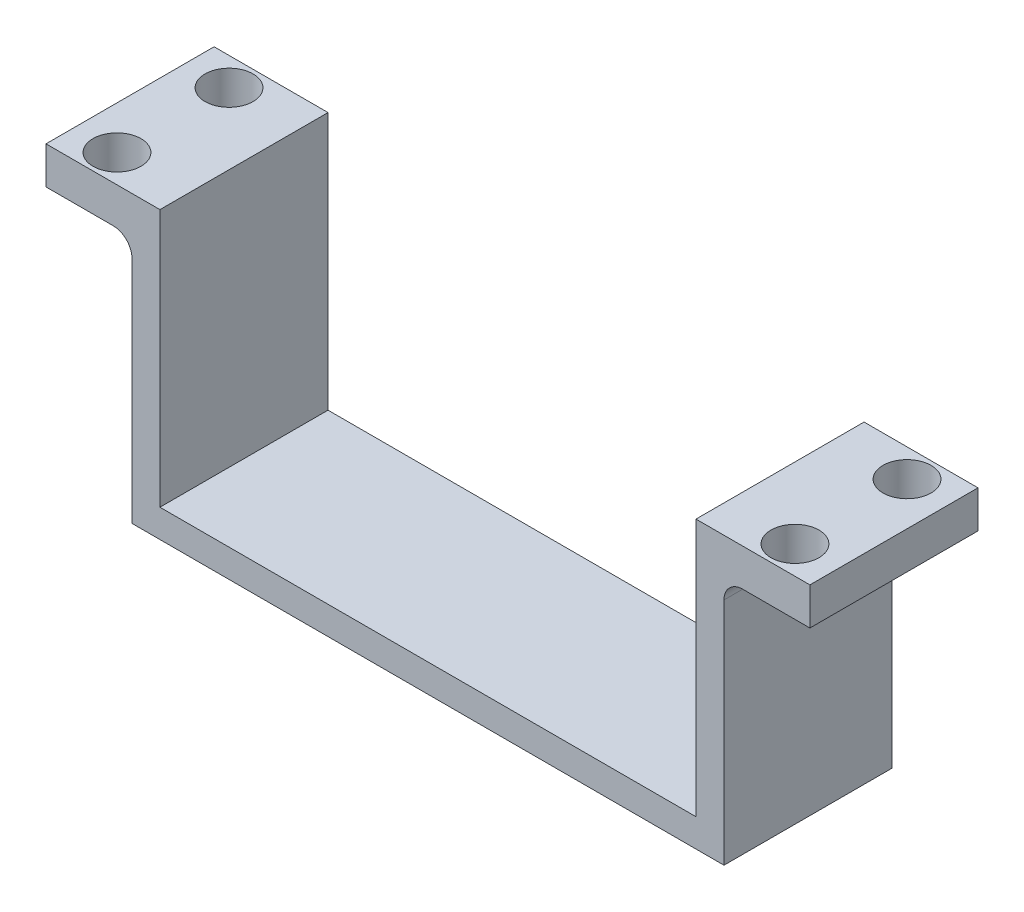
SolidWorks part; units mm, degrees
ref_plane "Front Plane" through (0, 0, 0) normal (0, 0, 1) x (1, 0, 0)
ref_plane "Top Plane" through (0, 0, 0) normal (0, 1, 0) x (1, 0, 0)
ref_plane "Right Plane" through (0, 0, 0) normal (1, 0, 0) x (0, 0, -1)
sketch "Sketch1" plane through (0, 0, 0) normal (0, 0, 1) x (1, 0, 0)
  line L0 (0, 0) -> (0, -35.052)
  line L1 (0, -35.052) -> (72.898, -35.052)
  line L2 (72.898, -35.052) -> (72.898, 0)
  line L3 (72.898, 0) -> (76.708, 0)
  line L4 (76.708, 0) -> (76.708, -38.862)
  line L5 (76.708, -38.862) -> (-3.81, -38.862)
  line L6 (-3.81, -38.862) -> (-3.81, 0)
  line L7 (-3.81, 0) -> (0, 0)
  dimension "D1" = 35.052
  dimension "D2" = 72.898
  dimension "D3" = 3.81
  dimension "D4" = 3.81
extrude "Boss-Extrude1" add sketch "Sketch1" along normal blind 22.86
sketch "Sketch2" plane through (0, 0, 0) normal (0, 1, 0) x (1, 0, 0)
  line L0 (0, 0) -> (-15.494, 0)
  line L1 (0, 0) -> (0, -22.86)
  line L2 (0, -22.86) -> (-15.494, -22.86)
  line L3 (-15.494, 0) -> (-15.494, -22.86)
  line L4 (-9.652, -3.81) -> (-9.652, -19.05) construction
  line L5 (0, -22.86) -> (0, 0) construction
  line L6 (-3.81, -22.86) -> (-3.81, 0) construction
  line L7 (0, 0) -> (-3.81, 0) construction
  line L8 (0, -22.86) -> (-3.81, -22.86) construction
  circle A0 centre (-9.652, -3.81) radius 3.2639
  circle A1 centre (-9.652, -19.05) radius 3.2639
  point P8 (-15.494, -11.43)
  point P9 (-9.652, -11.43)
  dimension "D1" = 6.5278
  dimension "D2" = 7.62
  dimension "D3" = 5.842
  dimension "D4" = 5.842
extrude "Boss-Extrude2" add sketch "Sketch2" against normal blind 5.08
ref_plane "Plane1" through (36.449, 0, 0) normal (1, 0, 0) x (0, 0, -1)
mirror "Mirror1" about plane through (36.449, 0, 0) normal (1, 0, 0) of "Boss-Extrude2"
fillet "Fillet1" radius 2.54 2 edges at (76.708, -5.08, 11.43) (-3.81, -5.08, 11.43)
